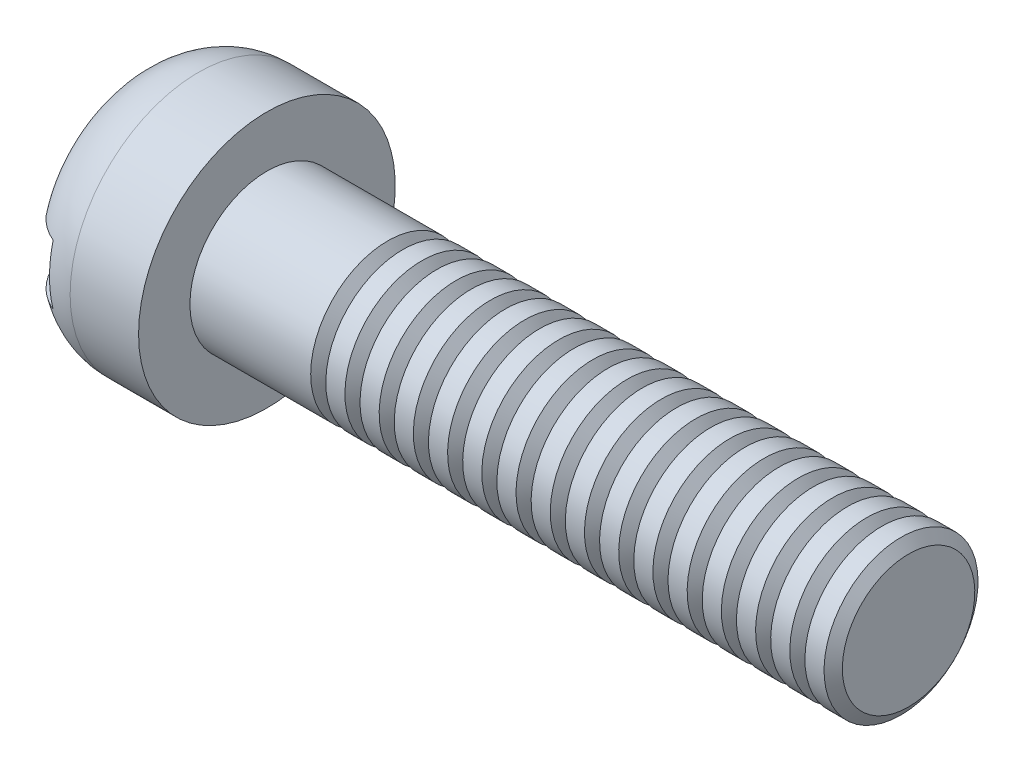
SolidWorks part; units mm, degrees
ref_plane "Plane1" through (0, 0, 0) normal (0, 0, 1) x (1, 0, 0)
ref_plane "Plane2" through (0, 0, 0) normal (0, 1, 0) x (1, 0, 0)
ref_plane "Plane3" through (0, 0, 0) normal (1, 0, 0) x (0, 0, -1)
sketch "BodySke" plane through (0, 0, 0) normal (0, 0, 1) x (1, 0, 0)
  line L0 (1.6, 0.9) -> (1.6, 1.5)
  line L1 (0, 0) -> (0, 0.7)
  line L2 (-25.4, 0) -> (127, 0) construction
  line L3 (9.1, 0) -> (0, 0)
  line L4 (1.6, 0.9) -> (9.1, 0.9)
  line L5 (9.1, 0.9) -> (9.1, 0)
  line L6 (0.8, 1.5) -> (1.6, 1.5)
  line L7 (1.6, -0.9) -> (9.1, -0.9) construction
  line L8 (0, -1.5) -> (1.6, -1.5) construction
  line L9 (2, 2.4875) -> (2, -7.0375) construction
  line L10 (3.1, 6.35) -> (3.1, -3.175) construction
  arc A0 (0, 0.7) -> (0.8, 1.5) centre (0.8, 0.7) cw
  point P15 (0, 1.5)
  dimension "Head_fillet_rad" = 0.8
  dimension "Diameter" = 1.8
  dimension "Length" = 7.5
  dimension "Head_ht" = 1.6
  dimension "Head_dia" = 3
  dimension "Advance" = 0.4
  dimension "Thread_nom" = 6
revolve "Base-Revolve" add sketch "BodySke" angle 360 about L2
cosmetic thread "ThreadCosmetic" [suppressed] parameters "Thread_length"=6, "Thread_minor"=1.548
sketch "Sketch2" plane through (0, 0, 0) normal (1, 0, 0) x (0, 0, -1)
  line L0 (1.5, -0.35) -> (-1.5, -0.35)
  line L1 (1.5, -0.35) -> (1.5, 0.35)
  line L2 (-1.5, 0.35) -> (1.5, 0.35)
  line L3 (-1.5, 0.35) -> (-1.5, -0.35)
  dimension "D1" = 3
  dimension "Slot_width" = 0.7
  dimension "D2" = 1.5
  dimension "D3" = 0.35
extrude "Slot" cut sketch "Sketch2" along normal blind 0.5
sketch "ThdSchSke" plane through (0, 0, 0) normal (0, 0, 1) x (1, 0, 0)
  line L0 (3.1, -0.774) -> (3.0118, -0.9)
  line L1 (3.1, -0.774) -> (3.1882, -0.9)
  line L2 (3.1882, -0.9) -> (3.1882, -1.35)
  line L3 (-3.175, 0) -> (5.1513, 0) construction
  line L5 (3.1882, -1.35) -> (3.0118, -1.35)
  line L6 (3.0118, -1.35) -> (3.0118, -0.9)
  point P6 (2, -0.774)
  point P7 (0, 0)
  point P10 (2, -0.774)
  dimension "Diameter" = 1.8
  dimension "SideAngle" = 55
  dimension "VeeAngle" = 70
  dimension "Thread_minor" = 1.548
  dimension "Overcut" = 2.7
  dimension "Start" = 3.1
revolve "ThreadSchematic" cut sketch "ThdSchSke" angle 360 about L3
pattern_linear "ThdSchPat" count 16 spacing 0.4 along (1, 0, 0) of "ThreadSchematic"
equation "\"D1@Sketch2\" = \"Head_dia@BodySke\""
equation "\"D2@Sketch2\" = \"D1@Sketch2\" / 2"
equation "\"D3@Sketch2\" = \"Slot_width@Sketch2\" / 2"
equation "\"Thread_length@ThreadCosmetic\" = ((sgn( (\"Length@BodySke\" - \"Advance@BodySke\" ) - \"Thread_nom@BodySke\" )-1)*( (\"Length@BodySke\" - \"Advance@BodySke\" ) - \"Thread_nom@BodySke\" ))/-2+ \"Thread_nom@BodySke\""
equation "\"Thread_minor@ThdSchSke\" = \"Thread_minor@ThreadCosmetic\""
equation "\"Diameter@ThdSchSke\" = \"Diameter@BodySke\""
equation "\"Overcut@ThdSchSke\"=\"Diameter@BodySke\" * 1.5"
equation "\"Start@ThdSchSke\" = \"Head_ht@BodySke\" + \"Length@BodySke\" - \"Thread_length@ThreadCosmetic\"  '---Non-countersunk---"
equation "\"Num_threads@ThdSchPat\" = int( \"Thread_length@ThreadCosmetic\" / \"Advance@BodySke\" + 0.999 )  + 1"
equation "\"Advance@ThdSchPat\" = \"Thread_length@ThreadCosmetic\" /  (\"Num_threads@ThdSchPat\" - 1) 'relax it"
